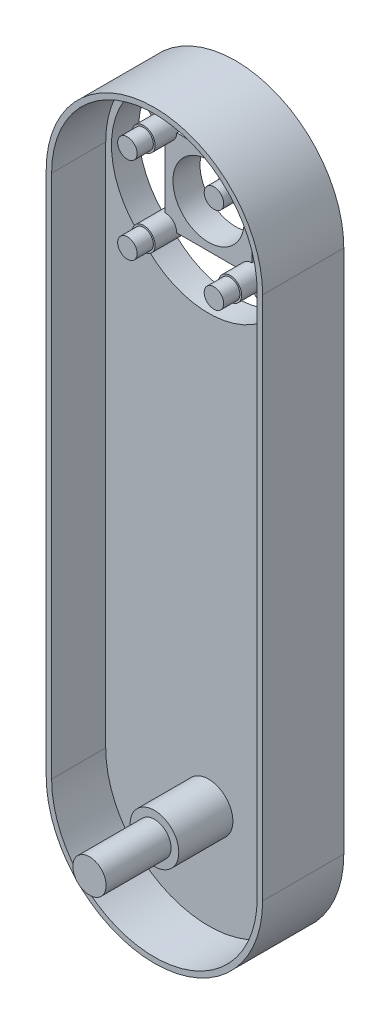
SolidWorks part; units mm, degrees
material "PLA"
ref_plane "Front Plane" through (0, 0, 0) normal (0, 0, 1) x (1, 0, 0)
ref_plane "Top Plane" through (0, 0, 0) normal (0, 1, 0) x (1, 0, 0)
ref_plane "Right Plane" through (0, 0, 0) normal (1, 0, 0) x (0, 0, -1)
sketch "Sketch2" plane through (0, 0, 0) normal (0, 0, 1) x (1, 0, 0)
  line L0 (-20, 0) -> (-20, -97)
  line L1 (20, 0) -> (20, -97)
  circle A0 centre (0, 0) radius 6.575
  arc A1 (20, 0) -> (-20, 0) centre (0, 0) ccw
  arc A2 (-20, -97) -> (20, -97) centre (0, -97) ccw
  dimension "D1" = 13.15
  dimension "D2" = 20
  dimension "D3" = 20
  dimension "D4" = 97
extrude "Boss-Extrude1" add sketch "Sketch2" along normal blind 5
sketch "Sketch3" plane through (0, 0, 5) normal (0, 0, 1) x (1, 0, 0)
  circle A0 centre (0, -97) radius 4.5
  dimension "D1" = 9
extrude "Boss-Extrude2" add sketch "Sketch3" along normal blind 10
sketch "Sketch4" plane through (0, 0, 5) normal (0, 0, 1) x (1, 0, 0)
  circle A0 centre (-8, 8) radius 2.125
  circle A1 centre (8, 8) radius 2.125
  circle A2 centre (8, -8) radius 2.125
  circle A3 centre (-8, -8) radius 2.125
  dimension "D6" = 4.25
  dimension "D1" = 16
  dimension "D2" = 16
  dimension "D3" = 16
  dimension "D4" = 8
  dimension "D5" = 8
extrude "Boss-Extrude3" add sketch "Sketch4" along normal blind 4
sketch "Sketch5" plane through (0, 0, 9) normal (0, 0, 1) x (1, 0, 0)
  circle A0 centre (-8, 8) radius 1.8
  circle A1 centre (8, 8) radius 1.8
  circle A2 centre (8, -8) radius 1.8
  circle A3 centre (-8, -8) radius 1.8
  dimension "D1" = 3.6
extrude "Boss-Extrude4" add sketch "Sketch5" along normal blind 3
sketch "Sketch6" plane through (0, 0, 5) normal (0, 0, 1) x (1, 0, 0)
  line L0 (20, -97) -> (20, 0) construction
  line L1 (-20, 0) -> (-20, -97) construction
  line L2 (20, -97) -> (20, 0)
  line L3 (-20, 0) -> (-20, -97)
  line L4 (-19, 0) -> (-19, -97)
  line L5 (19, -97) -> (19, 0)
  arc A0 (-20, -97) -> (20, -97) centre (0, -97) ccw construction
  arc A1 (20, 0) -> (-20, 0) centre (0, 0) ccw construction
  arc A2 (-20, -97) -> (20, -97) centre (0, -97) ccw
  arc A3 (20, 0) -> (-20, 0) centre (0, 0) ccw
  arc A4 (-19, -97) -> (19, -97) centre (0, -97) ccw
  arc A5 (19, 0) -> (-19, 0) centre (0, 0) ccw
  dimension "D1" = 1
extrude "Boss-Extrude5" add sketch "Sketch6" along normal blind 10
sketch "Sketch7" plane through (0, 0, 5) normal (0, 0, 1) x (1, 0, 0)
  line L0 (-10.125, 8) -> (-10.125, -8)
  line L1 (-8, -10.125) -> (8, -10.125)
  line L2 (10.125, -8) -> (10.125, 8)
  line L3 (8, 10.125) -> (-8, 10.125)
  line L4 (-5.875, 8) -> (5.875, 8)
  line L5 (8, 5.875) -> (8, -5.875)
  line L6 (5.875, -8) -> (-5.875, -8)
  line L7 (-8, 5.875) -> (-8, -5.875)
  circle A0 centre (-8, 8) radius 2.125 construction
  circle A1 centre (-8, 8) radius 2.125 construction
  circle A2 centre (-8, -8) radius 2.125 construction
  circle A3 centre (-8, -8) radius 2.125 construction
  circle A4 centre (8, -8) radius 2.125 construction
  circle A5 centre (8, -8) radius 2.125 construction
  circle A6 centre (8, 8) radius 2.125 construction
  circle A7 centre (8, 8) radius 2.125 construction
  arc A8 (-8, -10.125) -> (-5.875, -8) centre (-8, -8) ccw
  arc A9 (10.125, -8) -> (8, -5.875) centre (8, -8) ccw
  arc A10 (8, 10.125) -> (5.875, 8) centre (8, 8) ccw
  arc A11 (-10.125, 8) -> (-8, 5.875) centre (-8, 8) ccw
  arc A12 (-5.875, 8) -> (-8, 10.125) centre (-8, 8) ccw
  arc A13 (8, 5.875) -> (10.125, 8) centre (8, 8) ccw
  arc A14 (5.875, -8) -> (8, -10.125) centre (8, -8) ccw
  arc A15 (-8, -5.875) -> (-10.125, -8) centre (-8, -8) ccw
  dimension "D1" = 16
  dimension "D2" = 11.75
extrude "Cut-Extrude1" cut sketch "Sketch7" against normal blind 10
sketch "Sketch8" plane through (0, 0, 15) normal (0, 0, 1) x (1, 0, 0)
  circle A0 centre (0, -97) radius 3.075
  dimension "D1" = 6.15
extrude "Boss-Extrude6" add sketch "Sketch8" along normal blind 12
sketch "Sketch9" plane through (0, 0, 15) normal (0, 0, 1) x (1, 0, 0)
  line L0 (-20, 0) -> (-20, -97) construction
  line L1 (20, -97) -> (20, 0) construction
  line L2 (-20, 0) -> (-20, -97)
  line L3 (20, -97) -> (20, 0)
  arc A1 (20, 0) -> (-20, 0) centre (0, 0) ccw construction
  arc A3 (20, 0) -> (-20, 0) centre (0, 0) ccw
  arc A5 (19, -97) -> (-19, -97) centre (0, -97) ccw
  arc A6 (-20, -97) -> (20, -97) centre (0, -97) ccw construction
  arc A7 (-19, -97) -> (19, -97) centre (0, -97) ccw construction
  arc A8 (-20, -97) -> (20, -97) centre (0, -97) ccw
  arc A9 (-19, -97) -> (19, -97) centre (0, -97) ccw
sketch "Sketch10" plane through (0, 0, 0) normal (0, 0, -1) x (-1, 0, 0)
  line L0 (-8, 10.125) -> (-11.182, 13.307)
  line L1 (-8, 10.125) -> (8, 10.125) construction
  line L2 (-10.125, 8) -> (-13.307, 11.182)
  line L3 (8, 10.125) -> (11.182, 13.307)
  line L4 (10.125, 8) -> (13.307, 11.182)
  line L5 (10.125, -8) -> (13.307, -11.182)
  line L6 (8, -10.125) -> (11.182, -13.307)
  line L7 (-8, -10.125) -> (-11.182, -13.307)
  line L8 (-10.125, -8) -> (-13.307, -11.182)
  line L9 (-8, 10.125) -> (8, 10.125)
  line L10 (-10.125, -8) -> (-10.125, 8) construction
  line L11 (-10.125, -8) -> (-10.125, 8)
  line L12 (10.125, 8) -> (10.125, -8) construction
  line L13 (10.125, 8) -> (10.125, -8)
  line L14 (8, -10.125) -> (-8, -10.125) construction
  line L15 (8, -10.125) -> (-8, -10.125)
  arc A2 (-11.182, 13.307) -> (11.182, 13.307) centre (0, 2.125) cw
  arc A3 (13.307, 11.182) -> (13.307, -11.182) centre (2.125, 0) cw
  arc A4 (11.182, -13.307) -> (-11.182, -13.307) centre (0, -2.125) cw
  arc A5 (-13.307, -11.182) -> (-13.307, 11.182) centre (-2.125, 0) cw
  dimension "D2" = 15.8137
  dimension "D1" = 4.5
  dimension "D3" = 11.182
  dimension "D4" = 11.182
  dimension "D5" = 11.182
  dimension "D6" = 11.182
  dimension "D7" = 11.182
  dimension "D8" = 11.182
  dimension "D9" = 11.182
  dimension "D10" = 11.182
extrude "Cut-Extrude2" cut sketch "Sketch10" against normal blind 10
